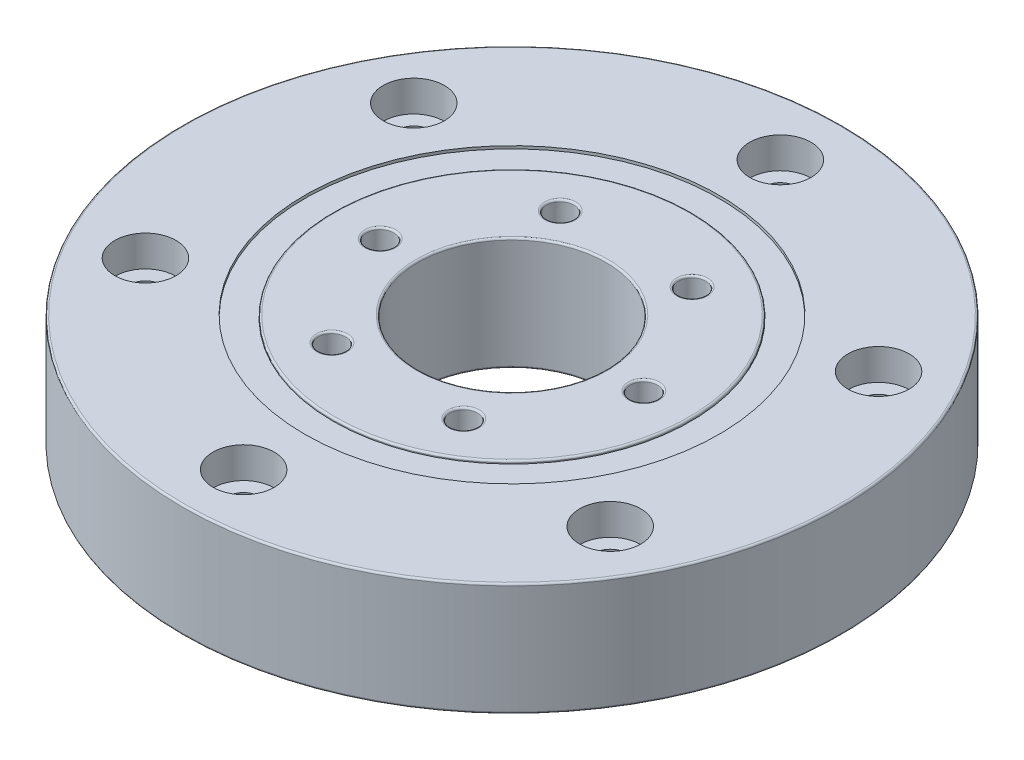
SolidWorks part; units mm, degrees
ref_plane "前视基准面" through (0, 0, 0) normal (0, 0, 1) x (1, 0, 0)
ref_plane "上视基准面" through (0, 0, 0) normal (0, 1, 0) x (1, 0, 0)
ref_plane "右视基准面" through (0, 0, 0) normal (1, 0, 0) x (0, 0, -1)
sketch "草图1" plane through (0, 0, 0) normal (0, 1, 0) x (1, 0, 0)
  line L1 (14, 0) -> (7, 12.1244) construction
  line L2 (7, 12.1244) -> (-7, 12.1244) construction
  line L3 (-7, 12.1244) -> (-14, 0) construction
  line L4 (-14, 0) -> (-7, -12.1244) construction
  line L5 (-7, -12.1244) -> (7, -12.1244) construction
  line L6 (7, -12.1244) -> (14, 0) construction
  line L7 (0, -28.5) -> (24.6817, -14.25) construction
  line L8 (24.6817, -14.25) -> (24.6817, 14.25) construction
  line L9 (24.6817, 14.25) -> (0, 28.5) construction
  line L10 (0, 28.5) -> (-24.6817, 14.25) construction
  line L11 (-24.6817, 14.25) -> (-24.6817, -14.25) construction
  line L12 (-24.6817, -14.25) -> (0, -28.5) construction
  circle A0 centre (0, 0) radius 10
  circle A1 centre (0, 0) radius 35
  circle A2 centre (0, 0) radius 14 construction
  circle A3 centre (0, 0) radius 28.5 construction
  circle A4 centre (0, 0) radius 12.1244 construction
  circle A5 centre (-7, 12.1244) radius 1.45
  circle A6 centre (7, 12.1244) radius 1.45
  circle A7 centre (14, 0) radius 1.45
  circle A8 centre (7, -12.1244) radius 1.45
  circle A9 centre (-7, -12.1244) radius 1.45
  circle A10 centre (-14, 0) radius 1.45
  circle A11 centre (0, 0) radius 24.6817 construction
  circle A12 centre (0, 28.5) radius 1.7
  circle A13 centre (24.6817, 14.25) radius 1.7
  circle A14 centre (24.6817, -14.25) radius 1.7
  circle A15 centre (0, -28.5) radius 1.7
  circle A16 centre (-24.6817, -14.25) radius 1.7
  circle A17 centre (-24.6817, 14.25) radius 1.7
  dimension "D1" = 20
  dimension "D2" = 70
  dimension "D3" = 28
  dimension "D4" = 57
  dimension "D5" = 2.9
  dimension "D6" = 3.4
extrude "凸台-拉伸1" add sketch "草图1" along normal mid plane 12
sketch "草图2" plane through (0, 6, 0) normal (0, 1, 0) x (1, 0, 0)
  circle A0 centre (0, 0) radius 19
  circle A1 centre (0, 0) radius 22
  dimension "D1" = 38
  dimension "D2" = 44
extrude "切除-拉伸1" cut sketch "草图2" against normal blind 0.3
sketch "草图3" plane through (0, -6, 0) normal (0, -1, 0) x (1, 0, 0)
  circle A0 centre (0, 0) radius 22
  circle A1 centre (0, 0) radius 19
  dimension "D1" = 44
  dimension "D2" = 38
extrude "切除-拉伸2" cut sketch "草图3" against normal blind 0.3
fillet "圆角1" radius 0.2 24 edges at (0, 6, 35) (-24.6817, -6, -12.55) (0, -6, -26.8) (24.6817, -6, -12.55) (24.6817, -6, 15.95) (0, -6, 30.2) (-24.6817, -6, 15.95) (0, -6, 35) (0, 6, 19) (-7, 6, 13.5744) (14, 6, 1.45) (-7, 6, -10.6744) (0, 6, 10) (7, 6, -10.6744) (7, 6, 13.5744) (-14, 6, 1.45) (0, -6, -19) (0, -6, 10) (-7, -6, -10.6744) (7, -6, -10.6744) (14, -6, 1.45) (7, -6, 13.5744) (-7, -6, 13.5744) (-14, -6, 1.45)
sketch "草图4" plane through (0, 6, 0) normal (0, 1, 0) x (1, 0, 0)
  circle A0 centre (0, 28.5) radius 3.25
  circle A1 centre (24.6817, 14.25) radius 3.25
  circle A2 centre (24.6817, -14.25) radius 3.25
  circle A3 centre (0, -28.5) radius 3.25
  circle A4 centre (-24.6817, -14.25) radius 3.25
  circle A5 centre (-24.6817, 14.25) radius 3.25
  dimension "D1" = 6.5
extrude "切除-拉伸3" cut sketch "草图4" against normal blind 3.3
